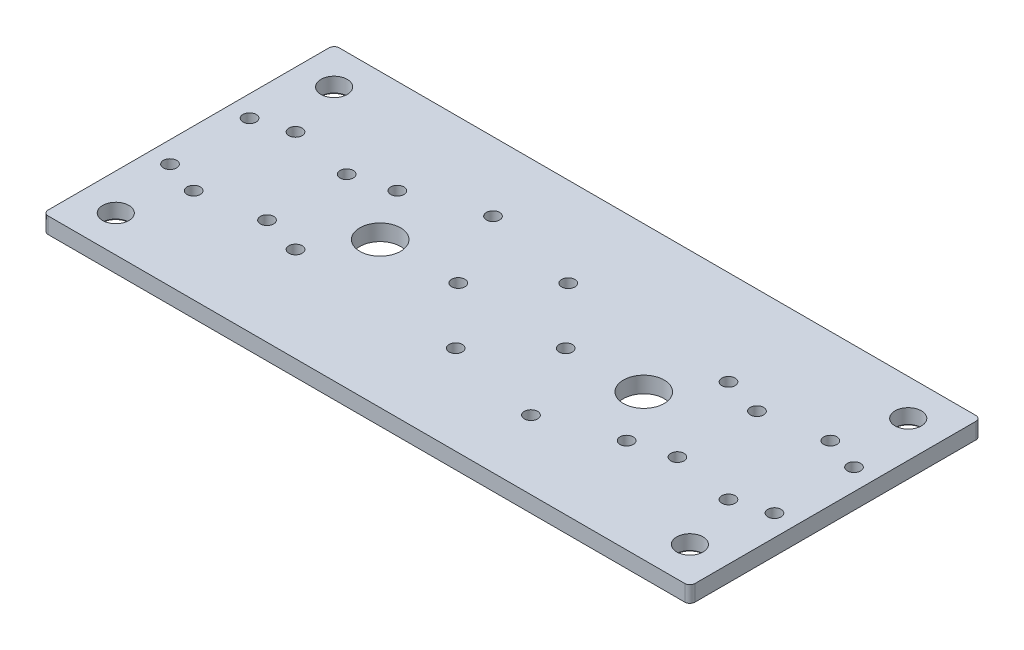
SolidWorks part; units mm, degrees
material "ABS"
ref_plane "Front Plane" through (0, 0, 0) normal (0, 0, 1) x (1, 0, 0)
ref_plane "Top Plane" through (0, 0, 0) normal (0, 1, 0) x (1, 0, 0)
ref_plane "Right Plane" through (0, 0, 0) normal (1, 0, 0) x (0, 0, -1)
sketch "Sketch1" plane through (0, 0, 0) normal (0, 1, 0) x (1, 0, 0)
  line L1 (-127, 57.15) -> (127, 57.15)
  line L2 (-127, 57.15) -> (-127, -57.15)
  line L3 (-127, -57.15) -> (127, -57.15)
  line L4 (127, 57.15) -> (127, -57.15)
  line L5 (-127, 57.15) -> (127, -57.15) construction
  line L6 (-127, -57.15) -> (127, 57.15) construction
  point P0 (0, 0)
  dimension "D1" = 254
  dimension "D2" = 114.3
extrude "Boss-Extrude1" add sketch "Sketch1" along normal blind 6.35 contours L1 L4 L3 L2
sketch "Sketch6" plane through (0, 6.35, 0) normal (0, 1, 0) x (1, 0, 0)
  point P0 (-80.5625, -15.621)
  point P1 (-80.5625, 15.621)
  point P3 (-118.6625, -15.621)
  point P5 (-118.6625, 15.621)
  point P7 (118.6625, -15.621)
  point P9 (80.5625, -15.621)
  point P11 (80.5625, 15.621)
  point P13 (118.6625, 15.621)
hole_wizard "M3 Clearance Hole1" positions "Sketch6" profile "Sketch7" hole size "M3" standard "ANSI Metric" end condition through all
sketch "Sketch7" plane through (-80.5625, 6.35, 15.621) normal (1, 0, 0) x (0, 0, 1)
  line L0 (0, 0) -> (0, 6.35)
  line L1 (0, 6.35) -> (2.6, 6.35)
  line L2 (2.6, 6.35) -> (2.6, 0)
  line L5 (2.6, 0) -> (0, 0)
  line L11 (0, -6.35) -> (0, 107.95) construction
  dimension "Thru Hole Dia." = 5.2
  dimension "Thru Hole Depth" = 6.35
sketch "Sketch8" plane through (0, 0, 0) normal (0, -1, 0) x (1, 0, 0)
  line L0 (127, 0) -> (-127, 0) construction
  line L1 (127, -57.15) -> (127, 57.15) construction
  line L2 (-127, -57.15) -> (-127, 57.15) construction
  line L3 (0, 57.15) -> (0, -57.15) construction
  line L4 (-127, 57.15) -> (127, 57.15) construction
  line L5 (-127, -57.15) -> (127, -57.15) construction
  point P0 (112.7125, 42.8625)
  point P13 (112.7125, -42.8625)
  point P14 (-112.7125, -42.8625)
  point P15 (-112.7125, 42.8625)
  dimension "D1" = 14.2875
  dimension "D2" = 14.2875
sketch "Sketch9" plane through (0, 0, 0) normal (0, -1, 0) x (-1, 0, 0)
  point P0 (-112.7125, 42.8625)
  point P3 (-112.7125, -42.8625)
  point P6 (112.7125, -42.8625)
  point P9 (112.7125, 42.8625)
hole_wizard "3/8 Clearance Hole1" positions "Sketch9" profile "Sketch10" hole size "3/8" standard "ANSI Inch" end condition through all
sketch "Sketch10" plane through (112.7125, 0, -42.8625) normal (1, 0, 0) x (0, 0, -1)
  line L0 (0, 0) -> (0, 6.35)
  line L1 (0, 6.35) -> (5.1587, 6.35)
  line L2 (5.1587, 6.35) -> (5.1587, 0.635)
  line L3 (5.1587, 0.635) -> (5.7937, 0)
  line L5 (5.7937, 0) -> (0, 0)
  line L6 (-5.1587, 0.635) -> (-5.7937, 0) construction
  line L11 (0, -6.35) -> (0, 107.95) construction
  dimension "Thru Hole Dia." = 10.3175
  dimension "Thru Hole Depth" = 6.35
  dimension "Near C'Sink Dia." = 11.5875
  dimension "Near C'Sink Angle" = 90
sketch "Sketch11" plane through (0, 0, 0) normal (0, -1, 0) x (1, 0, 0)
  line L0 (0, 57.15) -> (0, -57.15) construction
  line L1 (-127, 57.15) -> (127, 57.15) construction
  line L2 (-127, -57.15) -> (127, -57.15) construction
  line L3 (127, 0) -> (-127, 0) construction
  line L4 (127, -57.15) -> (127, 57.15) construction
  line L5 (-127, -57.15) -> (-127, 57.15) construction
  line L7 (105, 20) -> (65, 20) construction
  line L8 (105, 20) -> (105, -20) construction
  line L9 (105, -20) -> (65, -20) construction
  line L10 (65, 20) -> (65, -20) construction
  line L11 (105, 20) -> (65, -20) construction
  line L12 (105, -20) -> (65, 20) construction
  point P12 (85, 0)
  point P13 (65, -20)
  point P14 (105, 20)
  point P15 (105, -20)
  point P16 (65, 20)
  point P17 (-65, -20)
  point P18 (-65, 20)
  point P19 (-105, 20)
  point P20 (-105, -20)
  point P27 (65, 20)
  point P33 (65, -20)
  point P35 (105, -20)
  point P37 (105, 20)
  dimension "D1" = 40
  dimension "D2" = 40
  dimension "D3" = 65
hole_wizard "M3 Clearance Hole2" positions "Sketch11" profile "Sketch12" hole size "M3" standard "ANSI Metric"
sketch "Sketch12" plane through (105, 0, 20) normal (1, 0, 0) x (0, 0, -1)
  line L0 (0, 0) -> (0, 6.35)
  line L1 (0, 6.35) -> (2.6, 6.35)
  line L2 (2.6, 6.35) -> (2.6, 0)
  line L5 (2.6, 0) -> (0, 0)
  line L11 (0, -6.35) -> (0, 107.95) construction
  dimension "Thru Hole Dia." = 5.2
  dimension "Thru Hole Depth" = 6.35
fillet "Fillet1" radius 2 4 edges at (127, 3.175, 57.15) (127, 3.175, -57.15) (-127, 3.175, 57.15) (-127, 3.175, -57.15)
sketch "Sketch16" plane through (0, 0, 0) normal (0, -1, 0) x (1, 0, 0)
  line L0 (0, -57.15) -> (0, 57.15) construction
  line L1 (-125, -57.15) -> (125, -57.15) construction
  line L2 (-125, 57.15) -> (125, 57.15) construction
  line L4 (-40.15, -37) -> (-19.05, -37) construction
  line L5 (-40.15, -37) -> (-40.15, 6.35) construction
  line L6 (-40.15, 6.35) -> (-19.05, 6.35) construction
  line L7 (-19.05, -37) -> (-19.05, 6.35) construction
  line L9 (19.05, -6.35) -> (40.15, -6.35) construction
  line L10 (19.05, -6.35) -> (19.05, 37) construction
  line L11 (19.05, 37) -> (40.15, 37) construction
  line L12 (40.15, -6.35) -> (40.15, 37) construction
  line L13 (19.05, -6.35) -> (40.15, 37) construction
  line L14 (19.05, 37) -> (40.15, -6.35) construction
  line L16 (-10.95, -27.15) -> (10.95, -27.15) construction
  line L17 (-10.95, -27.15) -> (-10.95, 27.15) construction
  line L18 (-10.95, 27.15) -> (10.95, 27.15) construction
  line L19 (10.95, -27.15) -> (10.95, 27.15) construction
  line L20 (-10.95, -27.15) -> (10.95, 27.15) construction
  line L21 (-10.95, 27.15) -> (10.95, -27.15) construction
  point P11 (-21.65, -0.55)
  point P12 (-37.55, -30.1)
  point P57 (37.55, 30.1)
  point P59 (21.65, 0.55)
  point P93 (0, 22.1)
  point P96 (0, -22.1)
  point P100 (-10.95, 0)
  dimension "D1" = 43.35
  dimension "D2" = 21.1
  dimension "D3" = 19.05
  dimension "D4" = 2.6
  dimension "D5" = 36.45
  dimension "D6" = 2.6
  dimension "D7" = 36.45
  dimension "D8" = 21.1
  dimension "D9" = 43.35
  dimension "D10" = 50.8
  dimension "D11" = 19.05
  dimension "D12" = 2.6
  dimension "D13" = 36.45
  dimension "D14" = 50.8
  dimension "D15" = 2.6
  dimension "D16" = 36.45
  dimension "D17" = 54.3
  dimension "D18" = 21.9
  dimension "D19" = 27.15
  dimension "D20" = 10.95
  dimension "D21" = 22.1
  dimension "D22" = 22.1
hole_wizard "M3 Clearance Hole4" positions "Sketch16" profile "Sketch17" hole size "M3" standard "ANSI Metric" end condition through all
sketch "Sketch17" plane through (0, 0, -22.1) normal (1, 0, 0) x (0, 0, -1)
  line L0 (0, 0) -> (0, 6.35)
  line L1 (0, 6.35) -> (2.6, 6.35)
  line L2 (2.6, 6.35) -> (2.6, 0)
  line L5 (2.6, 0) -> (0, 0)
  line L11 (0, -6.35) -> (0, 107.95) construction
  dimension "Thru Hole Dia." = 5.2
  dimension "Thru Hole Depth" = 6.35
sketch "Sketch18" plane through (0, 0, 0) normal (0, -1, 0) x (1, 0, 0)
  line L0 (127, 0) -> (-127, 0) construction
  line L1 (0, 57.15) -> (0, -57.15) construction
  line L2 (-125, 57.15) -> (125, 57.15) construction
  line L3 (-125, -57.15) -> (125, -57.15) construction
  circle A0 centre (-51.75, 0) radius 8
  circle A1 centre (51.75, 0) radius 8
  dimension "D1" = 16
  dimension "D2" = 51.75
extrude "Cut-Extrude1" cut sketch "Sketch18" against normal through all
